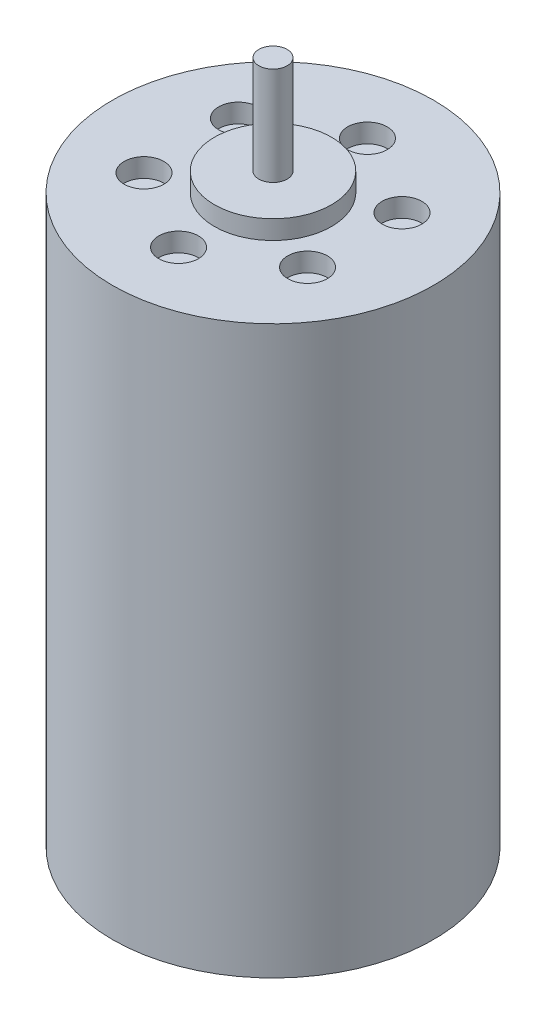
SolidWorks part; units mm, degrees
material "锌合金 7; AG40B; Zn-4Al-0.015Mg"
ref_plane "前视基准面" through (0, 0, 0) normal (0, 0, 1) x (1, 0, 0)
ref_plane "上视基准面" through (0, 0, 0) normal (0, 1, 0) x (1, 0, 0)
ref_plane "右视基准面" through (0, 0, 0) normal (1, 0, 0) x (0, 0, -1)
sketch "草图1" plane through (0, 0, 0) normal (0, 1, 0) x (1, 0, 0)
  circle A0 centre (0, 0) radius 8.5
extrude "凸台-拉伸1" add sketch "草图1" along normal blind 30
sketch "草图2" plane through (0, 30, 0) normal (0, 1, 0) x (1, 0, 0)
  circle A0 centre (0, 0) radius 3.1
extrude "凸台-拉伸2" add sketch "草图2" along normal blind 1
sketch "草图3" plane through (0, 31, 0) normal (0, 1, 0) x (1, 0, 0)
  circle A0 centre (0, 0) radius 0.75
extrude "凸台-拉伸3" add sketch "草图3" along normal blind 5.2
sketch "草图4" plane through (0, 30, 0) normal (0, 1, 0) x (1, 0, 0)
  line L0 (0, 5) -> (0, -5) construction
  line L1 (-4.3301, 2.5) -> (4.3301, -2.5) construction
  line L2 (-4.3301, -2.5) -> (4.3301, 2.5) construction
  circle A0 centre (0, 0) radius 5 construction
  circle A2 centre (0, 5) radius 1.05
  circle A3 centre (4.3301, 2.5) radius 1.05
  circle A4 centre (4.3301, -2.5) radius 1.05
  circle A5 centre (0, -5) radius 1.05
  circle A6 centre (-4.3301, -2.5) radius 1.05
  circle A7 centre (-4.3301, 2.5) radius 1.05
  dimension "D1" = 60
  dimension "D2" = 60
extrude "切除-拉伸1" cut sketch "草图4" against normal blind 1
